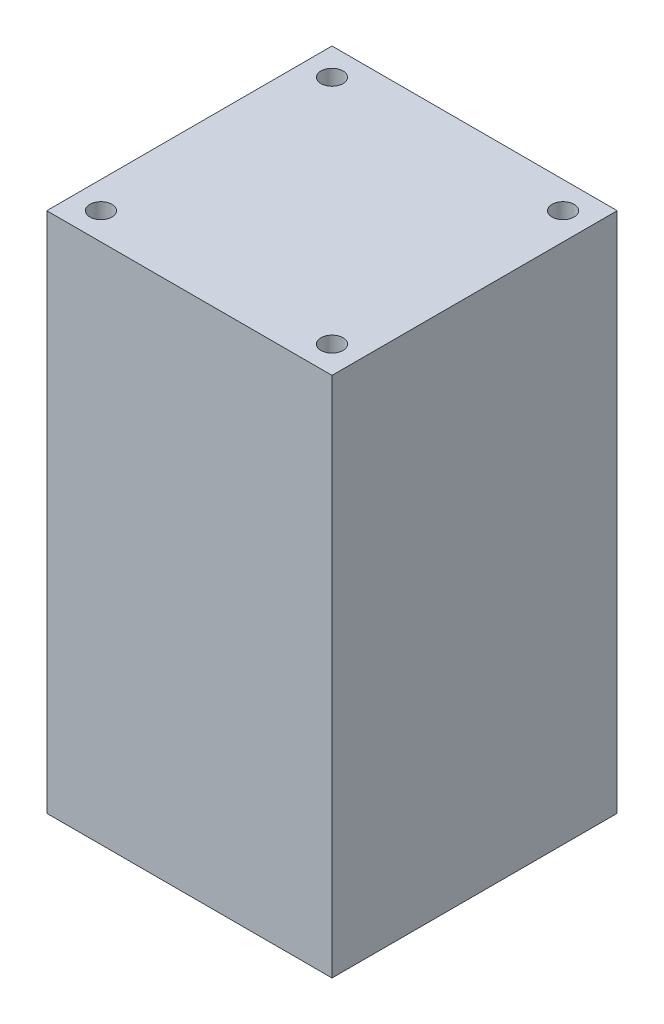
SolidWorks part; units mm, degrees
ref_plane "Front Plane" through (0, 0, 0) normal (0, 0, 1) x (1, 0, 0)
ref_plane "Top Plane" through (0, 0, 0) normal (0, 1, 0) x (1, 0, 0)
ref_plane "Right Plane" through (0, 0, 0) normal (1, 0, 0) x (0, 0, -1)
sketch "Sketch1" plane through (0, 0, 0) normal (0, 1, 0) x (1, 0, 0)
  line L1 (-44.5, -44.5) -> (44.5, -44.5) construction
  line L2 (-44.5, -44.5) -> (-44.5, 44.5) construction
  line L3 (-44.5, 44.5) -> (44.5, 44.5) construction
  line L4 (44.5, -44.5) -> (44.5, 44.5) construction
  line L5 (-44.5, -44.5) -> (44.5, 44.5) construction
  line L6 (-44.5, 44.5) -> (44.5, -44.5) construction
  line L7 (-54.93, -54.93) -> (54.93, -54.93)
  line L8 (-54.93, -54.93) -> (-54.93, 54.93)
  line L9 (-54.93, 54.93) -> (54.93, 54.93)
  line L10 (54.93, -54.93) -> (54.93, 54.93)
  line L11 (-54.93, -54.93) -> (54.93, 54.93) construction
  line L12 (-54.93, 54.93) -> (54.93, -54.93) construction
  circle A0 centre (-44.5, 44.5) radius 4.25
  circle A1 centre (44.5, 44.5) radius 4.25
  circle A2 centre (44.5, -44.5) radius 4.25
  circle A3 centre (-44.5, -44.5) radius 4.25
  point P0 (0, 0)
  point P10 (0, 0)
  dimension "D1" = 8.5
  dimension "D2" = 89
  dimension "D4" = 109.86
extrude "Boss-Extrude1" add sketch "Sketch1" against normal blind 201
